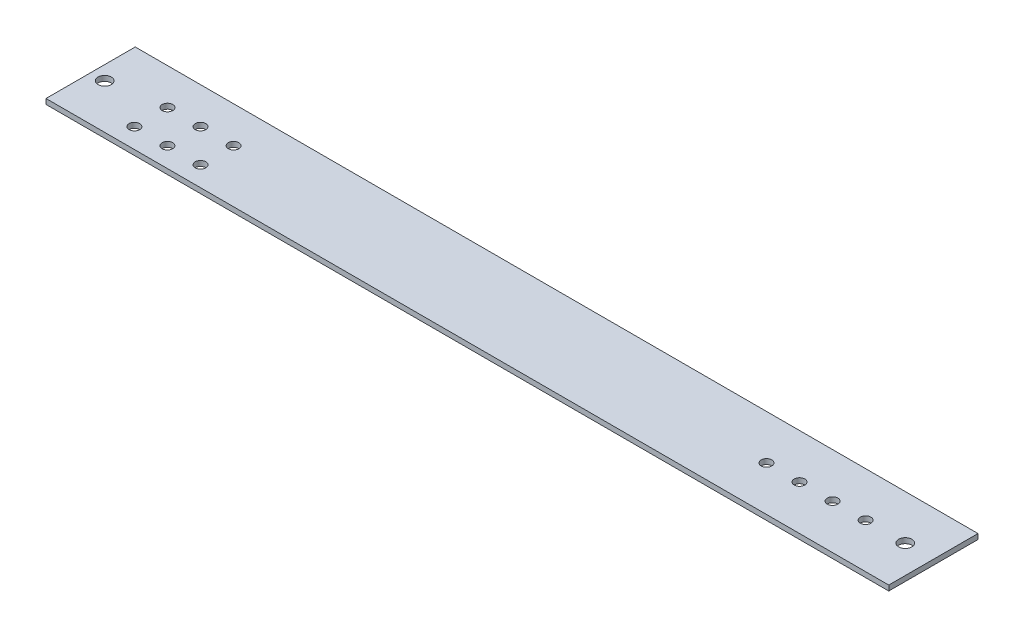
SolidWorks part; units mm, degrees
ref_plane "Front Plane" through (0, 0, 0) normal (0, 0, 1) x (1, 0, 0)
ref_plane "Top Plane" through (0, 0, 0) normal (0, 1, 0) x (1, 0, 0)
ref_plane "Right Plane" through (0, 0, 0) normal (1, 0, 0) x (0, 0, -1)
sketch "Sketch1" plane through (0, 0, 0) normal (0, 1, 0) x (1, 0, 0)
  line L1 (0, 6.858) -> (64.77, 6.858)
  line L2 (0, 6.858) -> (0, 0)
  line L3 (0, 0) -> (64.77, 0)
  line L4 (64.77, 6.858) -> (64.77, 0)
  dimension "D1" = 6.858
  dimension "D2" = 64.77
extrude "Boss-Extrude1" add sketch "Sketch1" along normal blind 0.4
sketch "Sketch2" plane through (0, 0.4, 0) normal (0, 1, 0) x (1, 0, 0)
  circle A0 centre (51.943, 3.429) radius 0.4064
  circle A1 centre (54.483, 3.429) radius 0.4064
  circle A2 centre (57.023, 3.429) radius 0.4064
  circle A3 centre (59.563, 3.429) radius 0.4064
  circle A4 centre (62.611, 3.429) radius 0.508
  circle A5 centre (10.3505, 4.064) radius 0.4064
  circle A6 centre (7.8105, 4.064) radius 0.4064
  circle A7 centre (5.2705, 4.064) radius 0.4064
  circle A8 centre (7.8105, 1.524) radius 0.4064
  circle A9 centre (5.2705, 1.524) radius 0.4064
  circle A10 centre (10.3505, 1.524) radius 0.4064
  circle A11 centre (1.0795, 3.429) radius 0.508
  point P0 (55.753, 3.429)
  point P11 (9.0805, 2.794)
  dimension "D1" = 3.81
  dimension "D3" = 1.27
  dimension "D5" = 3
  dimension "D4" = 1.27
  dimension "D2" = 4
  dimension "D6" = 2
extrude "Cut-Extrude1" cut sketch "Sketch2" against normal through all
